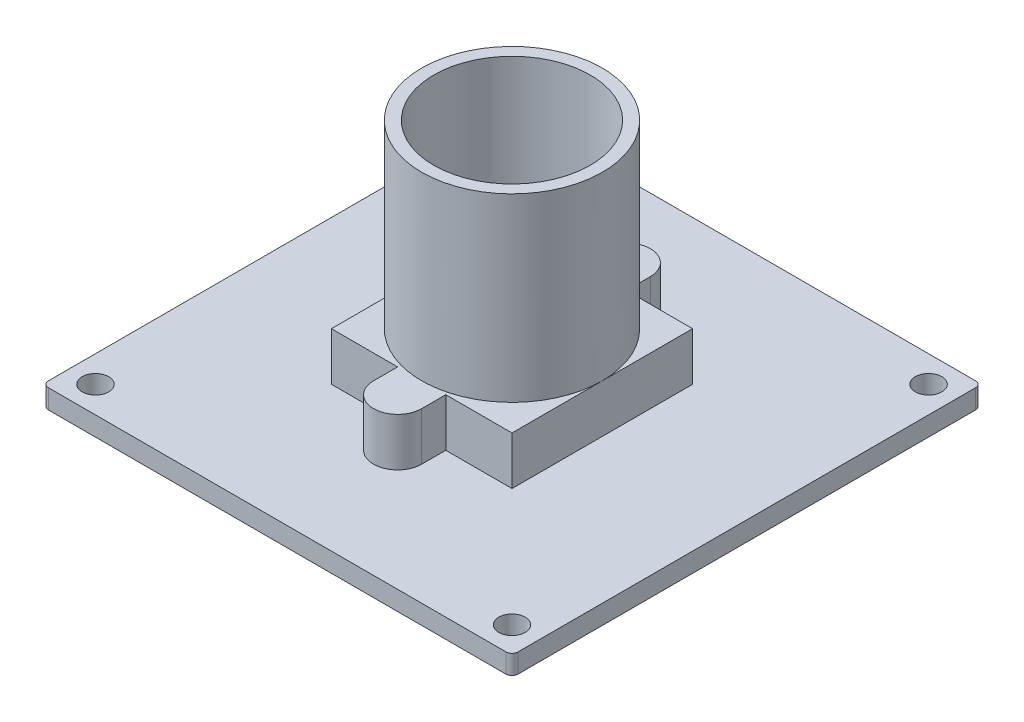
SolidWorks part; units mm, degrees
ref_plane "Front Plane" through (0, 0, 0) normal (0, 0, 1) x (1, 0, 0)
ref_plane "Top Plane" through (0, 0, 0) normal (0, 1, 0) x (1, 0, 0)
ref_plane "Right Plane" through (0, 0, 0) normal (1, 0, 0) x (0, 0, -1)
sketch "Sketch1" plane through (0, 0, 0) normal (0, 1, 0) x (1, 0, 0)
  line L1 (-19.5, 19.5) -> (19.5, 19.5)
  line L2 (-19.5, 19.5) -> (-19.5, -19.5)
  line L3 (-19.5, -19.5) -> (19.5, -19.5)
  line L4 (19.5, 19.5) -> (19.5, -19.5)
  line L5 (-19.5, 19.5) -> (19.5, -19.5) construction
  line L6 (-19.5, -19.5) -> (19.5, 19.5) construction
  point P0 (0, 0)
  dimension "D1" = 39
  dimension "D2" = 39
extrude "Boss-Extrude1" add sketch "Sketch1" along normal mid plane 1.6
fillet "Fillet1" radius 0.5 4 edges at (-19.5, 0, 19.5) (19.5, 0, 19.5) (19.5, 0, -19.5) (-19.5, 0, -19.5)
sketch "Sketch2" plane through (0, 0.8, 0) normal (0, 1, 0) x (1, 0, 0)
  line L0 (19, 19.5) -> (-19, 19.5) construction
  line L1 (-19.5, 19) -> (-19.5, -19) construction
  line L2 (0, 19.5) -> (0, -19.5) construction
  line L3 (-19, -19.5) -> (19, -19.5) construction
  line L4 (-19.5, 0) -> (19.5, 0) construction
  line L5 (19.5, -19) -> (19.5, 19) construction
  circle A0 centre (-17.3, 17.3) radius 1.1
  circle A1 centre (-17.3, -17.3) radius 1.1
  circle A2 centre (17.3, -17.3) radius 1.1
  circle A3 centre (17.3, 17.3) radius 1.1
  dimension "D1" = 2.2
  dimension "D2" = 2.2
  dimension "D3" = 2.2
extrude "Cut-Extrude1" cut sketch "Sketch2" against normal blind 1.6
sketch "Sketch3" plane through (0, 0.8, 0) normal (0, 1, 0) x (1, 0, 0)
  line L1 (-3.5, 3.5) -> (3.5, 3.5)
  line L2 (-3.5, 3.5) -> (-3.5, -3.5)
  line L3 (-3.5, -3.5) -> (3.5, -3.5)
  line L4 (3.5, 3.5) -> (3.5, -3.5)
  line L5 (-3.5, 3.5) -> (3.5, -3.5) construction
  line L6 (-3.5, -3.5) -> (3.5, 3.5) construction
  point P0 (0, 0)
  dimension "D1" = 7
  dimension "D2" = 7
extrude "Boss-Extrude2" add sketch "Sketch3" along normal blind 2
sketch "Sketch4" plane through (0, 0.8, 0) normal (0, 1, 0) x (1, 0, 0)
  line L0 (-2, 9.5) -> (-2, 7.5)
  line L1 (-7.5, 7.5) -> (-2, 7.5)
  line L2 (-7.5, 7.5) -> (-7.5, -7.5)
  line L3 (-7.5, -7.5) -> (-2, -7.5)
  line L4 (7.5, 7.5) -> (7.5, -7.5)
  line L5 (-7.5, 7.5) -> (7.5, -7.5) construction
  line L6 (-7.5, -7.5) -> (7.5, 7.5) construction
  line L7 (7, -7) -> (-7, -7)
  line L8 (7, -7) -> (7, 7)
  line L9 (7, 7) -> (-7, 7)
  line L10 (-7, -7) -> (-7, 7)
  line L11 (7, -7) -> (-7, 7) construction
  line L12 (7, 7) -> (-7, -7) construction
  line L13 (2, 9.5) -> (2, 7.5)
  line L14 (2, 7.5) -> (7.5, 7.5)
  line L15 (-7, 0) -> (7, 0) construction
  line L16 (2, -9.5) -> (2, -7.5)
  line L17 (-2, -9.5) -> (-2, -7.5)
  line L18 (2, -7.5) -> (7.5, -7.5)
  arc A0 (2, 9.5) -> (-2, 9.5) centre (0, 9.5) ccw
  arc A1 (2, -9.5) -> (-2, -9.5) centre (0, -9.5) cw
  point P0 (0, 0)
  point P6 (0, 0)
  dimension "D4" = 4
  dimension "D5" = 2
  dimension "D1" = 15
  dimension "D2" = 15
  dimension "D3" = 0.5
extrude "Boss-Extrude3" add sketch "Sketch4" along normal blind 4
sketch "Sketch5" plane through (0, 4.8, 0) normal (0, 1, 0) x (1, 0, 0)
  line L1 (-7.5, 7.5) -> (7.5, 7.5)
  line L2 (-7.5, 7.5) -> (-7.5, -7.5)
  line L3 (-7.5, -7.5) -> (7.5, -7.5)
  line L4 (7.5, 7.5) -> (7.5, -7.5)
  line L5 (-7.5, 7.5) -> (7.5, -7.5) construction
  line L6 (-7.5, -7.5) -> (7.5, 7.5) construction
  point P1 (0, 0)
extrude "Boss-Extrude4" add sketch "Sketch5" against normal blind 0.1
sketch "Sketch6" plane through (0, 4.8, 0) normal (0, 1, 0) x (1, 0, 0)
  line L0 (7.5, -7.5) -> (7.5, 7.5) construction
  circle A0 centre (0, 0) radius 7.5
extrude "Boss-Extrude5" add sketch "Sketch6" along normal blind 15
hole_wizard "M12 Clearance Hole1" positions "Sketch9" profile "Sketch10" hole size "M12" standard "ISO"
sketch "Sketch9" plane through (0, 19.8, 0) normal (0, 1, 0) x (1, 0, 0)
  point P0 (0, 0)
sketch "Sketch10" plane through (0, 19.8, 0) normal (1, 0, 0) x (0, 0, 1)
  line L0 (0, 0) -> (0, 15.1)
  line L1 (0, 15.1) -> (6.5, 15.1)
  line L2 (6.5, 15.1) -> (6.5, 0)
  line L5 (6.5, 0) -> (0, 0)
  line L11 (0, -6.35) -> (0, 107.95) construction
  dimension "Thru Hole Dia." = 13
  dimension "Thru Hole Depth" = 15.1
